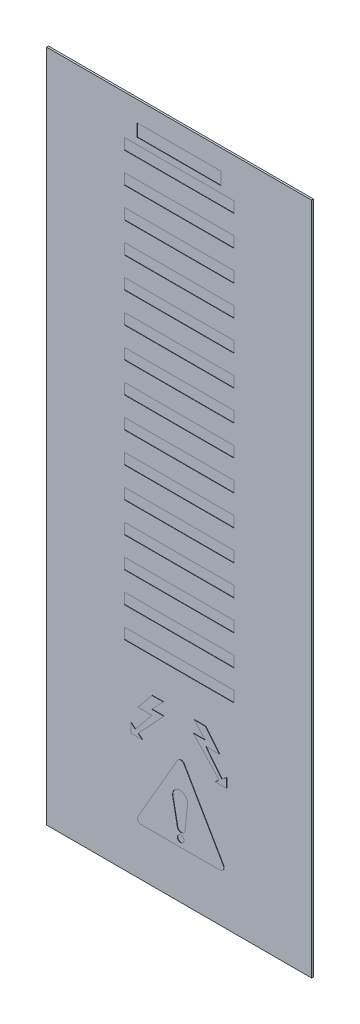
SolidWorks part; units mm, degrees
ref_plane "Alzado" through (0, 0, 0) normal (0, 0, 1) x (1, 0, 0)
ref_plane "Planta" through (0, 0, 0) normal (0, 1, 0) x (1, 0, 0)
ref_plane "Vista lateral" through (0, 0, 0) normal (1, 0, 0) x (0, 0, -1)
sketch "Croquis2" plane through (0, 0, 0) normal (0, 0, 1) x (1, 0, 0)
  line L1 (-35, -89) -> (35, -89)
  line L2 (-35, -89) -> (-35, 89)
  line L3 (-35, 89) -> (35, 89)
  line L4 (35, -89) -> (35, 89)
  line L5 (-35, -89) -> (35, 89) construction
  line L6 (-35, 89) -> (35, -89) construction
  point P0 (0, 0)
  dimension "D1" = 178
  dimension "D2" = 70
extrude "Saliente-Extruir1" add sketch "Croquis2" along normal blind 0.5
sketch "Croquis3" plane through (0, 0, 0.5) normal (0, 0, 1) x (1, 0, 0)
  line L0 (-9.8555, -76.3097) -> (10.9275, -76.3097)
  line L1 (11.7935, -74.8096) -> (1.4019, -56.8183)
  line L2 (-0.3299, -56.8183) -> (-10.7215, -74.8096)
  arc A0 (10.9275, -76.3097) -> (11.7935, -74.8096) centre (10.9275, -75.3097) ccw
  arc A1 (-9.8555, -76.3097) -> (-10.7215, -74.8096) centre (-9.8555, -75.3097) cw
  arc A2 (1.4019, -56.8183) -> (-0.3299, -56.8183) centre (0.536, -57.3184) ccw
  dimension "D1" = 1
extrude "Saliente-Extruir3" add sketch "Croquis3" along normal blind 0.1
sketch "Croquis4" plane through (0, 0, 0.5) normal (0, 0, 1) x (1, 0, 0)
  line L0 (-4.1078, -45.3278) -> (-7.0774, -45.3278)
  line L1 (-7.0774, -45.3278) -> (-10.7215, -49.8547)
  line L2 (-10.7215, -49.8547) -> (-7.0774, -49.8547)
  line L3 (-7.0774, -49.8547) -> (-11.4372, -55.2707)
  line L4 (-11.4372, -55.2707) -> (-12.6215, -54.3174)
  line L5 (-12.6215, -54.3174) -> (-12.6215, -56.7418)
  line L6 (-12.6215, -56.7418) -> (-9.6097, -56.7418)
  line L7 (-9.6097, -56.7418) -> (-10.7215, -55.8468)
  line L8 (-10.7215, -55.8468) -> (-3.908, -48.5208)
  line L9 (-3.908, -48.5208) -> (-7.0774, -48.5208)
  line L10 (-7.0774, -48.5208) -> (-4.1078, -45.3278)
  line L12 (9.6097, -56.7418) -> (10.7215, -55.8468)
  line L13 (12.6215, -56.7418) -> (9.6097, -56.7418)
  line L14 (12.6215, -54.3174) -> (12.6215, -56.7418)
  line L15 (11.4372, -55.2707) -> (12.6215, -54.3174)
  line L16 (7.0774, -49.8547) -> (11.4372, -55.2707)
  line L17 (10.7215, -55.8468) -> (3.908, -48.5208)
  line L18 (3.908, -48.5208) -> (7.0774, -48.5208)
  line L19 (10.7215, -49.8547) -> (7.0774, -49.8547)
  line L20 (7.0774, -45.3278) -> (10.7215, -49.8547)
  line L21 (4.1078, -45.3278) -> (7.0774, -45.3278)
  line L22 (7.0774, -48.5208) -> (4.1078, -45.3278)
sketch "Croquis6" plane through (0, 0, 0.5) normal (0, 0, 1) x (1, 0, 0)
sketch "Croquis7" plane through (0, 0, 0.5) normal (0, 0, 1) x (1, 0, 0)
  line L1 (-11.0884, 80.343) -> (11.0884, 80.343)
  line L2 (-11.0884, 80.343) -> (-11.0884, 83.6508)
  line L3 (-11.0884, 83.6508) -> (11.0884, 83.6508)
  line L4 (11.0884, 80.343) -> (11.0884, 83.6508)
  line L5 (-11.0884, 80.343) -> (11.0884, 83.6508) construction
  line L6 (-11.0884, 83.6508) -> (11.0884, 80.343) construction
  point P0 (0, 81.9969)
extrude "Cortar-Extruir1" cut sketch "Croquis7" against normal blind 0.1
sketch "Croquis8" plane through (0, 0, 0.5) normal (0, 0, 1) x (1, 0, 0)
  point P0 (0, 75.7948)
  point P5 (0, 70.7948)
  point P11 (0, 65.7948)
  dimension "D1" = 3
sketch "Croquis9" plane through (0, 0, 0.5) normal (0, 0, 1) x (1, 0, 0)
  point P0 (0, 61.7366)
  point P6 (0, 31.7366)
  point P11 (0, 1.7366)
  point P16 (0, -28.2634)
  dimension "D1" = 4
sketch "Croquis10" plane through (0, 0, 0.5) normal (0, 0, 1) x (1, 0, 0)
  point P0 (0, 57.8585)
  point P6 (0, 42.8585)
  point P11 (0, 27.8585)
  point P16 (0, 12.8585)
  point P21 (0, -2.1415)
  point P26 (0, -17.1415)
  point P31 (0, -32.1415)
  dimension "D1" = 7
sketch "Croquis11" plane through (0, 0, 0.5) normal (0, 0, 1) x (1, 0, 0)
  point P0 (0, 53.6432)
sketch "Croquis12" plane through (0, 0, 0.6) normal (0, 0, 1) x (1, 0, 0)
  line L0 (-0.3487, -71.9727) -> (-1.6286, -65.4259)
  line L2 (2.382, -65.2784) -> (1.6785, -71.9518)
  circle A0 centre (0.538, -74.3321) radius 0.8847
  arc A1 (1.6785, -71.9518) -> (-0.3487, -71.9727) centre (0.6637, -71.8449) cw
  arc A2 (2.382, -65.2784) -> (-1.6286, -65.4259) centre (0.3767, -65.3521) ccw
extrude "Cortar-Extruir6" cut sketch "Croquis12" against normal blind 0.1
extrude "Saliente-Extruir7" add sketch "Croquis4" along normal blind 0.1
sketch "Croquis14" plane through (0, 0, 0.5) normal (0, 0, 1) x (1, 0, 0)
  line L0 (-14.4757, 67.707) -> (14.4757, 70.594) construction
  line L1 (-14.4757, 75.707) -> (14.4757, 75.707)
  line L2 (-14.4757, 75.707) -> (-14.4757, 78.594)
  line L3 (-14.4757, 78.594) -> (14.4757, 78.594)
  line L4 (14.4757, 75.707) -> (14.4757, 78.594)
  line L5 (-14.4757, 75.707) -> (14.4757, 78.594) construction
  line L6 (-14.4757, 78.594) -> (14.4757, 75.707) construction
  line L7 (-14.4757, 70.594) -> (14.4757, 67.707) construction
  line L8 (-14.4757, 67.707) -> (-14.4757, 70.594)
  line L9 (-14.4757, 67.707) -> (14.4757, 67.707)
  line L10 (14.4757, 67.707) -> (14.4757, 70.594)
  line L11 (-14.4757, 70.594) -> (14.4757, 70.594)
  line L12 (-14.4757, 59.707) -> (14.4757, 62.594) construction
  line L13 (-14.4757, 62.594) -> (14.4757, 59.707) construction
  line L14 (-14.4757, 59.707) -> (-14.4757, 62.594)
  line L15 (-14.4757, 59.707) -> (14.4757, 59.707)
  line L16 (14.4757, 59.707) -> (14.4757, 62.594)
  line L17 (-14.4757, 62.594) -> (14.4757, 62.594)
  line L18 (-14.4757, 51.707) -> (14.4757, 54.594) construction
  line L19 (-14.4757, 54.594) -> (14.4757, 51.707) construction
  line L20 (-14.4757, 51.707) -> (-14.4757, 54.594)
  line L21 (-14.4757, 51.707) -> (14.4757, 51.707)
  line L22 (14.4757, 51.707) -> (14.4757, 54.594)
  line L23 (-14.4757, 54.594) -> (14.4757, 54.594)
  line L24 (-14.4757, 43.707) -> (14.4757, 46.594) construction
  line L25 (-14.4757, 46.594) -> (14.4757, 43.707) construction
  line L26 (-14.4757, 43.707) -> (-14.4757, 46.594)
  line L27 (-14.4757, 43.707) -> (14.4757, 43.707)
  line L28 (14.4757, 43.707) -> (14.4757, 46.594)
  line L29 (-14.4757, 46.594) -> (14.4757, 46.594)
  line L30 (-14.4757, 35.707) -> (14.4757, 38.594) construction
  line L31 (-14.4757, 38.594) -> (14.4757, 35.707) construction
  line L32 (-14.4757, 35.707) -> (-14.4757, 38.594)
  line L33 (-14.4757, 35.707) -> (14.4757, 35.707)
  line L34 (14.4757, 35.707) -> (14.4757, 38.594)
  line L35 (-14.4757, 38.594) -> (14.4757, 38.594)
  line L36 (-14.4757, 27.707) -> (14.4757, 30.594) construction
  line L37 (-14.4757, 30.594) -> (14.4757, 27.707) construction
  line L38 (-14.4757, 27.707) -> (-14.4757, 30.594)
  line L39 (-14.4757, 27.707) -> (14.4757, 27.707)
  line L40 (14.4757, 27.707) -> (14.4757, 30.594)
  line L41 (-14.4757, 30.594) -> (14.4757, 30.594)
  line L42 (-14.4757, 19.707) -> (14.4757, 22.594) construction
  line L43 (-14.4757, 22.594) -> (14.4757, 19.707) construction
  line L44 (-14.4757, 19.707) -> (-14.4757, 22.594)
  line L45 (-14.4757, 19.707) -> (14.4757, 19.707)
  line L46 (14.4757, 19.707) -> (14.4757, 22.594)
  line L47 (-14.4757, 22.594) -> (14.4757, 22.594)
  line L48 (-14.4757, 11.707) -> (14.4757, 14.594) construction
  line L49 (-14.4757, 14.594) -> (14.4757, 11.707) construction
  line L50 (-14.4757, 11.707) -> (-14.4757, 14.594)
  line L51 (-14.4757, 11.707) -> (14.4757, 11.707)
  line L52 (14.4757, 11.707) -> (14.4757, 14.594)
  line L53 (-14.4757, 14.594) -> (14.4757, 14.594)
  line L54 (-14.4757, 3.707) -> (14.4757, 6.594) construction
  line L55 (-14.4757, 6.594) -> (14.4757, 3.707) construction
  line L56 (-14.4757, 3.707) -> (-14.4757, 6.594)
  line L57 (-14.4757, 3.707) -> (14.4757, 3.707)
  line L58 (14.4757, 3.707) -> (14.4757, 6.594)
  line L59 (-14.4757, 6.594) -> (14.4757, 6.594)
  line L60 (-14.4757, -4.293) -> (14.4757, -1.406) construction
  line L61 (-14.4757, -1.406) -> (14.4757, -4.293) construction
  line L62 (-14.4757, -4.293) -> (-14.4757, -1.406)
  line L63 (-14.4757, -4.293) -> (14.4757, -4.293)
  line L64 (14.4757, -4.293) -> (14.4757, -1.406)
  line L65 (-14.4757, -1.406) -> (14.4757, -1.406)
  line L66 (-14.4757, -12.293) -> (14.4757, -9.406) construction
  line L67 (-14.4757, -9.406) -> (14.4757, -12.293) construction
  line L68 (-14.4757, -12.293) -> (-14.4757, -9.406)
  line L69 (-14.4757, -12.293) -> (14.4757, -12.293)
  line L70 (14.4757, -12.293) -> (14.4757, -9.406)
  line L71 (-14.4757, -9.406) -> (14.4757, -9.406)
  line L72 (-14.4757, -20.293) -> (14.4757, -17.406) construction
  line L73 (-14.4757, -17.406) -> (14.4757, -20.293) construction
  line L74 (-14.4757, -20.293) -> (-14.4757, -17.406)
  line L75 (-14.4757, -20.293) -> (14.4757, -20.293)
  line L76 (14.4757, -20.293) -> (14.4757, -17.406)
  line L77 (-14.4757, -17.406) -> (14.4757, -17.406)
  line L78 (-14.4757, -28.293) -> (14.4757, -25.406) construction
  line L79 (-14.4757, -25.406) -> (14.4757, -28.293) construction
  line L80 (-14.4757, -28.293) -> (-14.4757, -25.406)
  line L81 (-14.4757, -28.293) -> (14.4757, -28.293)
  line L82 (14.4757, -28.293) -> (14.4757, -25.406)
  line L83 (-14.4757, -25.406) -> (14.4757, -25.406)
  line L84 (-14.4757, -36.293) -> (14.4757, -33.406) construction
  line L85 (-14.4757, -33.406) -> (14.4757, -36.293) construction
  line L86 (-14.4757, -36.293) -> (-14.4757, -33.406)
  line L87 (-14.4757, -36.293) -> (14.4757, -36.293)
  line L88 (14.4757, -36.293) -> (14.4757, -33.406)
  line L89 (-14.4757, -33.406) -> (14.4757, -33.406)
  point P0 (0, 77.1505)
  point P6 (0, 69.1505)
  point P11 (0, 61.1505)
  point P16 (0, 53.1505)
  point P21 (0, 45.1505)
  point P26 (0, 37.1505)
  point P31 (0, 29.1505)
  point P36 (0, 21.1505)
  point P41 (0, 13.1505)
  point P46 (0, 5.1505)
  point P51 (0, -2.8495)
  point P56 (0, -10.8495)
  point P61 (0, -18.8495)
  point P66 (0, -26.8495)
  point P71 (0, -34.8495)
  dimension "D1" = 15
extrude "Cortar-Extruir9" cut sketch "Croquis14" against normal blind 0.1
